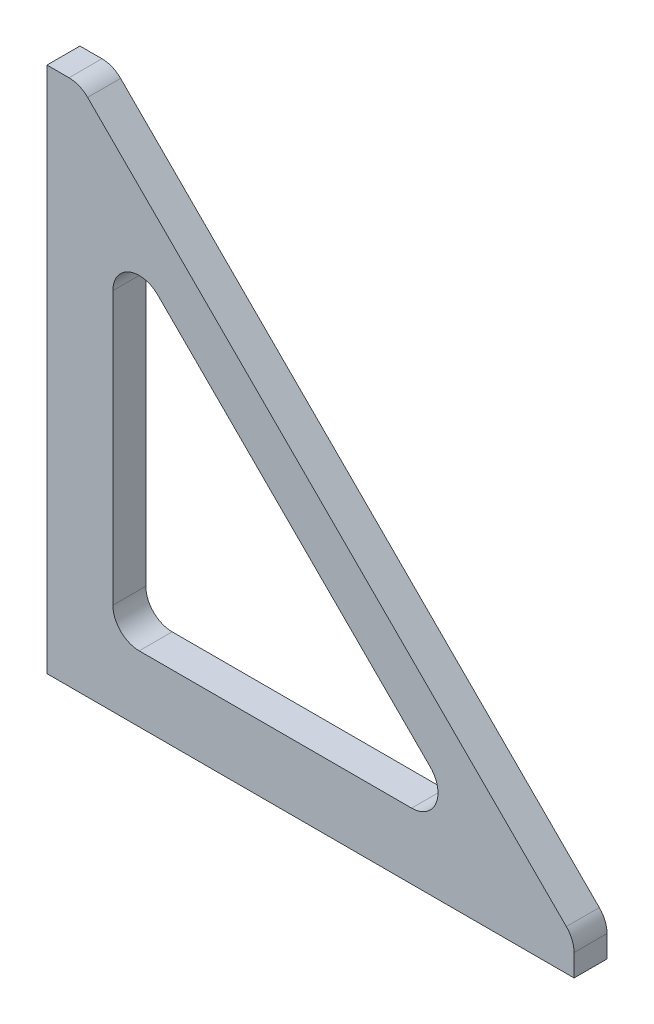
SolidWorks part; units mm, degrees
material "AISI 1020"
ref_plane "X-Y Datum" through (0, 0, 0) normal (0, 0, 1) x (1, 0, 0)
ref_plane "X-Z Datum" through (0, 0, 0) normal (0, 1, 0) x (1, 0, 0)
ref_plane "Y-Z Datum" through (0, 0, 0) normal (1, 0, 0) x (0, 0, -1)
sketch "Sketch1" plane through (0, 0, 0) normal (0, 0, 1) x (1, 0, 0)
  line L17 (0, 0) -> (0, 50.8)
  line L18 (0, -55) -> (0, 55) construction
  line L20 (3.175, 50.8) -> (50.8, 3.175)
  line L21 (50.8, 3.175) -> (50.8, 0)
  line L22 (55, 0) -> (-55, 0) construction
  line L23 (50.8, 0) -> (0, 0)
  line L24 (0, 50.8) -> (3.175, 50.8)
  dimension "D1" = 50.8
  dimension "D2" = 50.8
  dimension "D3" = 3.175
  dimension "D4" = 3.175
extrude "Boss-Extrude1" add sketch "Sketch1" along normal blind 3.175 contours L23 L17 L24 L20 L21
sketch "Sketch7" plane through (0, 0, 3.175) normal (0, 0, 1) x (1, 0, 0)
  line L0 (6.35, 41.275) -> (6.35, 6.35)
  line L1 (6.35, 6.35) -> (41.275, 6.35)
  line L2 (41.275, 6.35) -> (6.35, 41.275)
  line L3 (0, 0) -> (0, 50.8) construction
  line L4 (50.8, 0) -> (0, 0) construction
  dimension "D1" = 6.35
  dimension "D2" = 6.35
  dimension "D3" = 34.925
  dimension "D4" = 34.925
extrude "Cut-Extrude1" cut sketch "Sketch7" against normal up to surface (3.175 mm away) up to face at (20.955, 20.955, 0)
fillet "Fillet4" radius 2.54 2 edges at (3.175, 50.8, 1.5875) (50.8, 3.175, 1.5875)
fillet "Fillet5" radius 2.54 3 edges at (41.275, 6.35, 1.5875) (6.35, 6.35, 1.5875) (6.35, 41.275, 1.5875)
